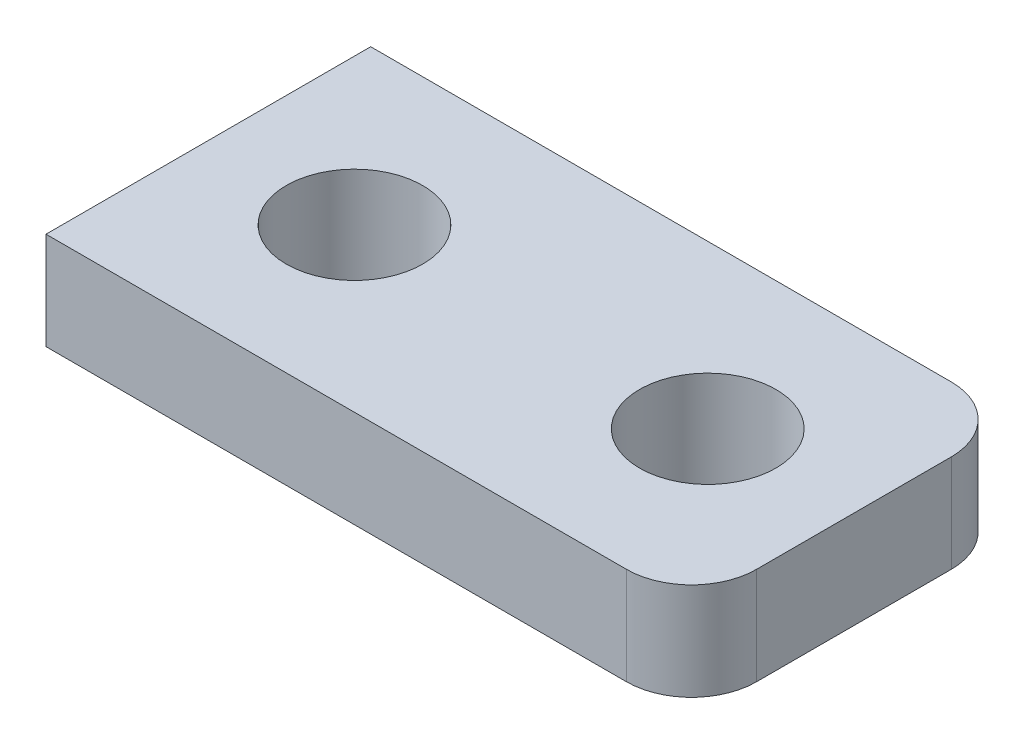
SolidWorks part; units mm, degrees
material "ABS"
ref_plane "Front Plane" through (0, 0, 0) normal (0, 0, 1) x (1, 0, 0)
ref_plane "Top Plane" through (0, 0, 0) normal (0, 1, 0) x (1, 0, 0)
ref_plane "Right Plane" through (0, 0, 0) normal (1, 0, 0) x (0, 0, -1)
sketch "Sketch1" plane through (0, 0, 0) normal (0, 1, 0) x (1, 0, 0)
  line L1 (0, 0) -> (19.88, 0)
  line L2 (0, 0) -> (0, 10)
  line L3 (0, 10) -> (19.88, 10)
  line L4 (19.88, 0) -> (19.88, 10)
  dimension "D1" = 19.88
  dimension "D2" = 10
extrude "Boss-Extrude1" add sketch "Sketch1" along normal blind 3
fillet "Fillet1" radius 2 2 edges at (19.88, 1.5, 0) (19.88, 1.5, -10)
sketch "Sketch2" plane through (0, 3, 0) normal (0, 1, 0) x (1, 0, 0)
  line L0 (0, 5) -> (19.88, 5) construction
  line L1 (0, 10) -> (0, 0) construction
  line L2 (19.88, 2) -> (19.88, 8) construction
  circle A0 centre (4.5, 5) radius 2.1
  circle A1 centre (15.38, 5) radius 2.1
  dimension "D3" = 4.2
  dimension "D4" = 4.2
  dimension "D1" = 4.5
  dimension "D2" = 4.5
extrude "Cut-Extrude1" cut sketch "Sketch2" against normal blind 3
